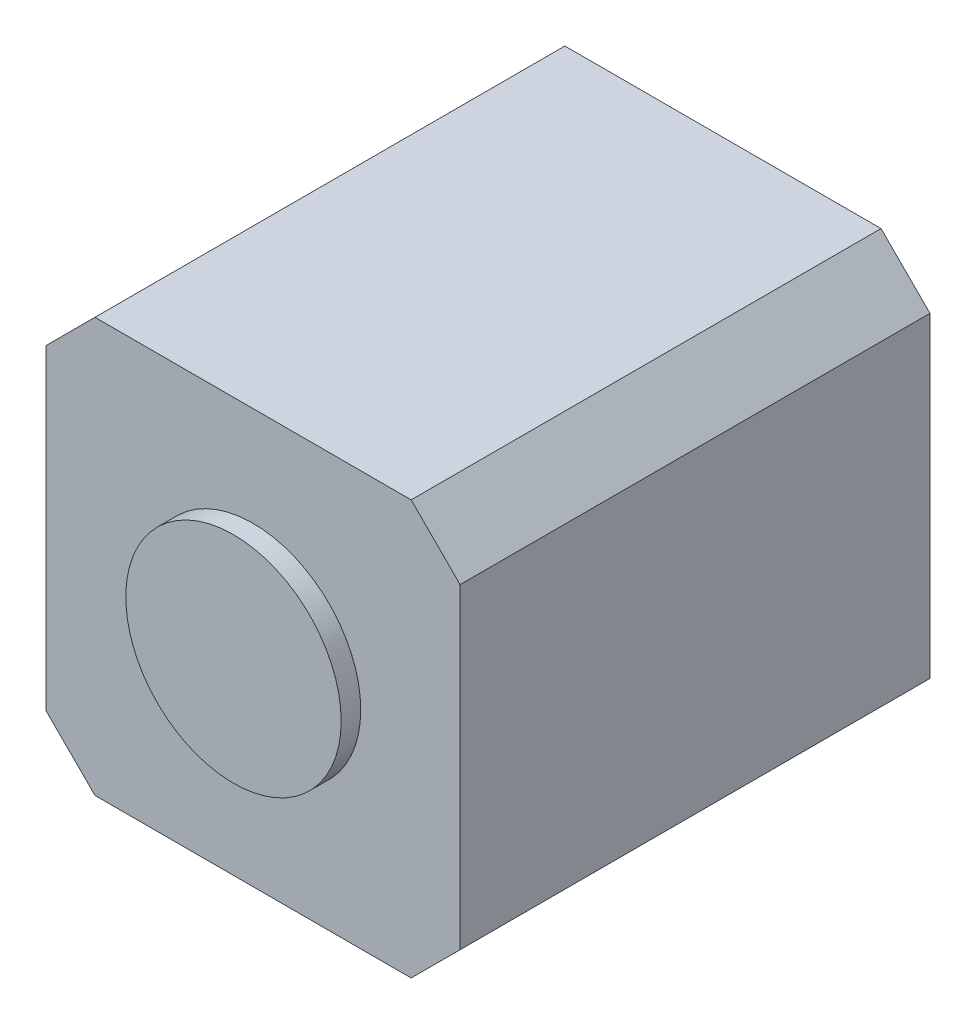
SolidWorks part; units mm, degrees
ref_plane "Front Plane" through (0, 0, 0) normal (0, 0, 1) x (1, 0, 0)
ref_plane "Top Plane" through (0, 0, 0) normal (0, 1, 0) x (1, 0, 0)
ref_plane "Right Plane" through (0, 0, 0) normal (1, 0, 0) x (0, 0, -1)
sketch "Sketch1" plane through (0, 0, 0) normal (0, 0, 1) x (1, 0, 0)
  line L1 (0, 0) -> (42.3, 0)
  line L2 (0, 0) -> (0, -42.3)
  line L3 (0, -42.3) -> (42.3, -42.3)
  line L4 (42.3, 0) -> (42.3, -42.3)
  dimension "D1" = 42.3
  dimension "D2" = 42.3
extrude "Boss-Extrude1" add sketch "Sketch1" along normal blind 48
sketch "Sketch2" plane through (0, 0, 48) normal (0, 0, 1) x (1, 0, 0)
  line L0 (21.15, 0) -> (21.15, -42.3) construction
  line L1 (42.3, 0) -> (0, 0) construction
  line L2 (0, -42.3) -> (42.3, -42.3) construction
  circle A0 centre (21.15, -21.15) radius 11
  dimension "D1" = 22
extrude "Boss-Extrude2" add sketch "Sketch2" along normal blind 2
chamfer "Chamfer1" distance 5 angle 45 4 edges at (42.3, -42.3, 24) (42.3, 0, 24) (0, -42.3, 24) (0, 0, 24)
sketch "Sketch5" plane through (0, 0, 48) normal (0, 0, 1) x (1, 0, 0)
  line L0 (5.65, -5.65) -> (36.65, -5.65) construction
  line L1 (21.15, -21.15) -> (21.15, 0) construction
  line L2 (37.3, 0) -> (5, 0) construction
  line L3 (42.3, -21.15) -> (0, -21.15) construction
  line L4 (0, -5) -> (0, -37.3) construction
  line L5 (5.65, -36.65) -> (36.65, -36.65) construction
  circle A0 centre (36.65, -5.65) radius 1.5
  circle A1 centre (5.65, -5.65) radius 1.5
  circle A2 centre (36.65, -36.65) radius 1.5
  circle A3 centre (5.65, -36.65) radius 1.5
  point P6 (21.15, -5.65)
  point P17 (21.15, -21.15)
  dimension "D1" = 31
  dimension "D3" = 3
  dimension "D2" = 15.5
